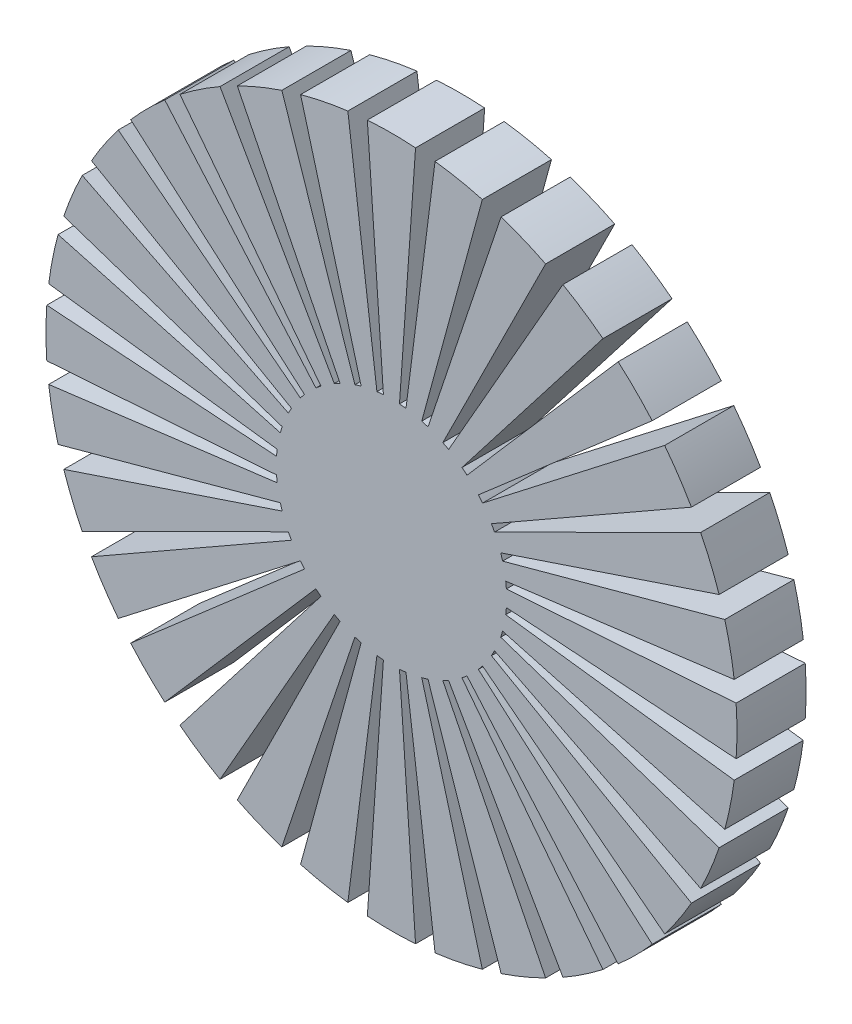
SolidWorks part; units mm, degrees
ref_plane "Front Plane" through (0, 0, 0) normal (0, 0, 1) x (1, 0, 0)
ref_plane "Top Plane" through (0, 0, 0) normal (0, 1, 0) x (1, 0, 0)
ref_plane "Right Plane" through (0, 0, 0) normal (1, 0, 0) x (0, 0, -1)
sketch "Sketch1" plane through (0, 0, 0) normal (0, 0, 1) x (1, 0, 0)
  line L0 (0, 0) -> (0, 150) construction
  line L1 (-3.4878, 49.8782) -> (-10.4635, 149.6346)
  line L2 (3.4878, 49.8782) -> (10.4635, 149.6346)
  line L3 (6.3099, 49.6002) -> (18.9298, 148.8007)
  line L4 (13.1516, 48.2394) -> (39.4547, 144.7181)
  line L5 (15.8652, 47.4162) -> (47.5957, 142.2485)
  line L6 (22.3099, 44.7467) -> (66.9297, 134.2402)
  line L7 (24.8108, 43.4099) -> (74.4325, 130.2298)
  line L8 (30.6109, 39.5345) -> (91.8326, 118.6034)
  line L9 (32.803, 37.7355) -> (98.4089, 113.2064)
  line L10 (37.7355, 32.803) -> (113.2064, 98.4089)
  line L11 (39.5345, 30.6109) -> (118.6034, 91.8326)
  line L12 (43.4099, 24.8108) -> (130.2298, 74.4325)
  line L13 (44.7467, 22.3099) -> (134.2402, 66.9297)
  line L14 (47.4162, 15.8652) -> (142.2485, 47.5957)
  line L15 (48.2394, 13.1516) -> (144.7181, 39.4547)
  line L16 (49.6002, 6.3099) -> (148.8007, 18.9298)
  line L17 (49.8782, 3.4878) -> (149.6346, 10.4635)
  line L18 (49.8782, -3.4878) -> (149.6346, -10.4635)
  line L19 (49.6002, -6.3099) -> (148.8007, -18.9298)
  line L20 (48.2394, -13.1516) -> (144.7181, -39.4547)
  line L21 (47.4162, -15.8652) -> (142.2485, -47.5957)
  line L22 (44.7467, -22.3099) -> (134.2402, -66.9297)
  line L23 (43.4099, -24.8108) -> (130.2298, -74.4325)
  line L24 (39.5345, -30.6109) -> (118.6034, -91.8326)
  line L25 (37.7355, -32.803) -> (113.2064, -98.4089)
  line L26 (32.803, -37.7355) -> (98.4089, -113.2064)
  line L27 (30.6109, -39.5345) -> (91.8326, -118.6034)
  line L28 (24.8108, -43.4099) -> (74.4325, -130.2298)
  line L29 (22.3099, -44.7467) -> (66.9297, -134.2402)
  line L30 (15.8652, -47.4162) -> (47.5957, -142.2485)
  line L31 (13.1516, -48.2394) -> (39.4547, -144.7181)
  line L32 (6.3099, -49.6002) -> (18.9298, -148.8007)
  line L33 (3.4878, -49.8782) -> (10.4635, -149.6346)
  line L34 (-3.4878, -49.8782) -> (-10.4635, -149.6346)
  line L35 (-6.3099, -49.6002) -> (-18.9298, -148.8007)
  line L36 (-13.1516, -48.2394) -> (-39.4547, -144.7181)
  line L37 (-15.8652, -47.4162) -> (-47.5957, -142.2485)
  line L38 (-22.3099, -44.7467) -> (-66.9297, -134.2402)
  line L39 (-24.8108, -43.4099) -> (-74.4325, -130.2298)
  line L40 (-30.6109, -39.5345) -> (-91.8326, -118.6034)
  line L41 (-32.803, -37.7355) -> (-98.4089, -113.2064)
  line L42 (-37.7355, -32.803) -> (-113.2064, -98.4089)
  line L43 (-39.5345, -30.6109) -> (-118.6034, -91.8326)
  line L44 (-43.4099, -24.8108) -> (-130.2298, -74.4325)
  line L45 (-44.7467, -22.3099) -> (-134.2402, -66.9297)
  line L46 (-47.4162, -15.8652) -> (-142.2485, -47.5957)
  line L47 (-48.2394, -13.1516) -> (-144.7181, -39.4547)
  line L48 (-49.6002, -6.3099) -> (-148.8007, -18.9298)
  line L49 (-49.8782, -3.4878) -> (-149.6346, -10.4635)
  line L50 (-49.8782, 3.4878) -> (-149.6346, 10.4635)
  line L51 (-49.6002, 6.3099) -> (-148.8007, 18.9298)
  line L52 (-48.2394, 13.1516) -> (-144.7181, 39.4547)
  line L53 (-47.4162, 15.8652) -> (-142.2485, 47.5957)
  line L54 (-44.7467, 22.3099) -> (-134.2402, 66.9297)
  line L55 (-43.4099, 24.8108) -> (-130.2298, 74.4325)
  line L56 (-39.5345, 30.6109) -> (-118.6034, 91.8326)
  line L57 (-37.7355, 32.803) -> (-113.2064, 98.4089)
  line L58 (-32.803, 37.7355) -> (-98.4089, 113.2064)
  line L59 (-30.6109, 39.5345) -> (-91.8326, 118.6034)
  line L60 (-24.8108, 43.4099) -> (-74.4325, 130.2298)
  line L61 (-22.3099, 44.7467) -> (-66.9297, 134.2402)
  line L62 (-15.8652, 47.4162) -> (-47.5957, 142.2485)
  line L63 (-13.1516, 48.2394) -> (-39.4547, 144.7181)
  line L64 (-6.3099, 49.6002) -> (-18.9298, 148.8007)
  arc A0 (10.4635, 149.6346) -> (-10.4635, 149.6346) centre (0, 0) ccw
  arc A1 (-3.4878, 49.8782) -> (-6.3099, 49.6002) centre (0, 0) ccw
  arc A2 (39.4547, 144.7181) -> (18.9298, 148.8007) centre (0, 0) ccw
  arc A3 (66.9297, 134.2402) -> (47.5957, 142.2485) centre (0, 0) ccw
  arc A4 (91.8326, 118.6034) -> (74.4325, 130.2298) centre (0, 0) ccw
  arc A5 (113.2064, 98.4089) -> (98.4089, 113.2064) centre (0, 0) ccw
  arc A6 (130.2298, 74.4325) -> (118.6034, 91.8326) centre (0, 0) ccw
  arc A7 (142.2485, 47.5957) -> (134.2402, 66.9297) centre (0, 0) ccw
  arc A8 (148.8007, 18.9298) -> (144.7181, 39.4547) centre (0, 0) ccw
  arc A9 (149.6346, -10.4635) -> (149.6346, 10.4635) centre (0, 0) ccw
  arc A10 (144.7181, -39.4547) -> (148.8007, -18.9298) centre (0, 0) ccw
  arc A11 (134.2402, -66.9297) -> (142.2485, -47.5957) centre (0, 0) ccw
  arc A12 (118.6034, -91.8326) -> (130.2298, -74.4325) centre (0, 0) ccw
  arc A13 (98.4089, -113.2064) -> (113.2064, -98.4089) centre (0, 0) ccw
  arc A14 (74.4325, -130.2298) -> (91.8326, -118.6034) centre (0, 0) ccw
  arc A15 (47.5957, -142.2485) -> (66.9297, -134.2402) centre (0, 0) ccw
  arc A16 (18.9298, -148.8007) -> (39.4547, -144.7181) centre (0, 0) ccw
  arc A17 (-10.4635, -149.6346) -> (10.4635, -149.6346) centre (0, 0) ccw
  arc A18 (-39.4547, -144.7181) -> (-18.9298, -148.8007) centre (0, 0) ccw
  arc A19 (-66.9297, -134.2402) -> (-47.5957, -142.2485) centre (0, 0) ccw
  arc A20 (-91.8326, -118.6034) -> (-74.4325, -130.2298) centre (0, 0) ccw
  arc A21 (-113.2064, -98.4089) -> (-98.4089, -113.2064) centre (0, 0) ccw
  arc A22 (-130.2298, -74.4325) -> (-118.6034, -91.8326) centre (0, 0) ccw
  arc A23 (-142.2485, -47.5957) -> (-134.2402, -66.9297) centre (0, 0) ccw
  arc A24 (-148.8007, -18.9298) -> (-144.7181, -39.4547) centre (0, 0) ccw
  arc A25 (-149.6346, 10.4635) -> (-149.6346, -10.4635) centre (0, 0) ccw
  arc A26 (-144.7181, 39.4547) -> (-148.8007, 18.9298) centre (0, 0) ccw
  arc A27 (-134.2402, 66.9297) -> (-142.2485, 47.5957) centre (0, 0) ccw
  arc A28 (-118.6034, 91.8326) -> (-130.2298, 74.4325) centre (0, 0) ccw
  arc A29 (-98.4089, 113.2064) -> (-113.2064, 98.4089) centre (0, 0) ccw
  arc A30 (-74.4325, 130.2298) -> (-91.8326, 118.6034) centre (0, 0) ccw
  arc A31 (-47.5957, 142.2485) -> (-66.9297, 134.2402) centre (0, 0) ccw
  arc A32 (-18.9298, 148.8007) -> (-39.4547, 144.7181) centre (0, 0) ccw
  arc A33 (-13.1516, 48.2394) -> (-15.8652, 47.4162) centre (0, 0) ccw
  arc A34 (-22.3099, 44.7467) -> (-24.8108, 43.4099) centre (0, 0) ccw
  arc A35 (-30.6109, 39.5345) -> (-32.803, 37.7355) centre (0, 0) ccw
  arc A36 (-37.7355, 32.803) -> (-39.5345, 30.6109) centre (0, 0) ccw
  arc A37 (-43.4099, 24.8108) -> (-44.7467, 22.3099) centre (0, 0) ccw
  arc A38 (-47.4162, 15.8652) -> (-48.2394, 13.1516) centre (0, 0) ccw
  arc A39 (-49.6002, 6.3099) -> (-49.8782, 3.4878) centre (0, 0) ccw
  arc A40 (-49.8782, -3.4878) -> (-49.6002, -6.3099) centre (0, 0) ccw
  arc A41 (-48.2394, -13.1516) -> (-47.4162, -15.8652) centre (0, 0) ccw
  arc A42 (-44.7467, -22.3099) -> (-43.4099, -24.8108) centre (0, 0) ccw
  arc A43 (-39.5345, -30.6109) -> (-37.7355, -32.803) centre (0, 0) ccw
  arc A44 (-32.803, -37.7355) -> (-30.6109, -39.5345) centre (0, 0) ccw
  arc A45 (-24.8108, -43.4099) -> (-22.3099, -44.7467) centre (0, 0) ccw
  arc A46 (-15.8652, -47.4162) -> (-13.1516, -48.2394) centre (0, 0) ccw
  arc A47 (-6.3099, -49.6002) -> (-3.4878, -49.8782) centre (0, 0) ccw
  arc A48 (3.4878, -49.8782) -> (6.3099, -49.6002) centre (0, 0) ccw
  arc A49 (13.1516, -48.2394) -> (15.8652, -47.4162) centre (0, 0) ccw
  arc A50 (22.3099, -44.7467) -> (24.8108, -43.4099) centre (0, 0) ccw
  arc A51 (30.6109, -39.5345) -> (32.803, -37.7355) centre (0, 0) ccw
  arc A52 (37.7355, -32.803) -> (39.5345, -30.6109) centre (0, 0) ccw
  arc A53 (43.4099, -24.8108) -> (44.7467, -22.3099) centre (0, 0) ccw
  arc A54 (49.6002, -6.3099) -> (49.8782, -3.4878) centre (0, 0) ccw
  arc A55 (49.8782, 3.4878) -> (49.6002, 6.3099) centre (0, 0) ccw
  arc A56 (48.2394, 13.1516) -> (47.4162, 15.8652) centre (0, 0) ccw
  arc A57 (44.7467, 22.3099) -> (43.4099, 24.8108) centre (0, 0) ccw
  arc A58 (39.5345, 30.6109) -> (37.7355, 32.803) centre (0, 0) ccw
  arc A59 (32.803, 37.7355) -> (30.6109, 39.5345) centre (0, 0) ccw
  arc A60 (24.8108, 43.4099) -> (22.3099, 44.7467) centre (0, 0) ccw
  arc A61 (15.8652, 47.4162) -> (13.1516, 48.2394) centre (0, 0) ccw
  arc A62 (6.3099, 49.6002) -> (3.4878, 49.8782) centre (0, 0) ccw
  arc A63 (47.4162, -15.8652) -> (48.2394, -13.1516) centre (0, 0) ccw
  point P11 (0, 0)
  point P135 (0, 0)
  dimension "D1" = 4
  dimension "D2" = 4
  dimension "D3" = 32
extrude "Boss-Extrude1" add sketch "Sketch1" along normal blind 30
